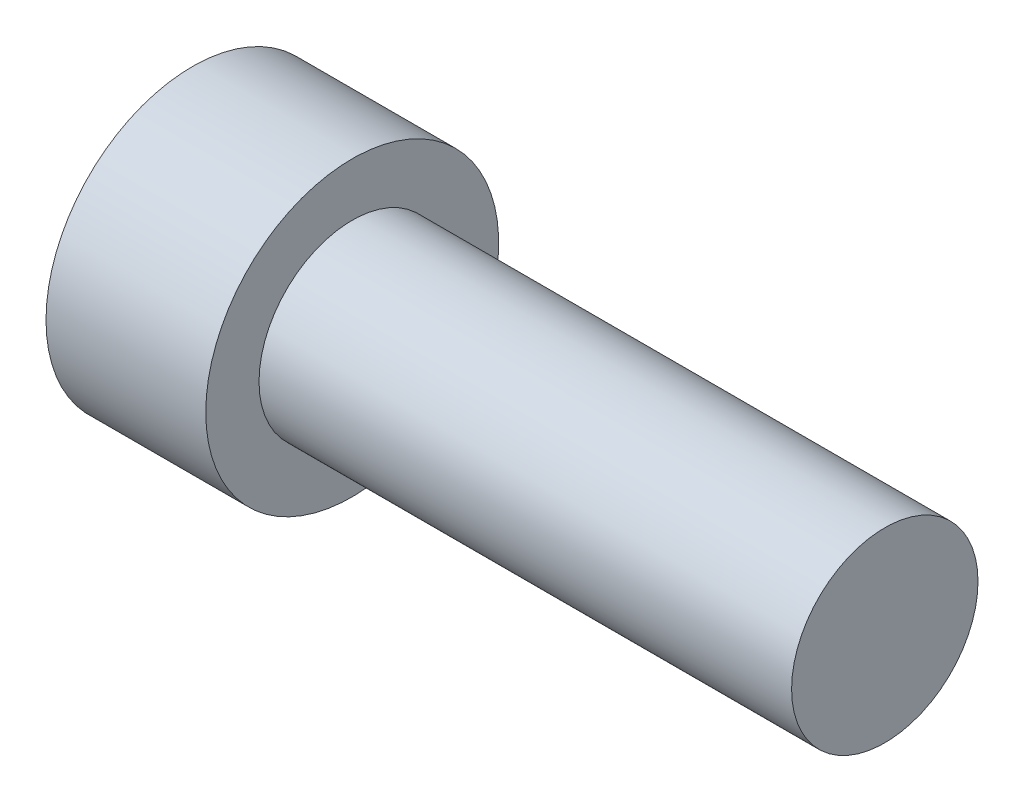
SolidWorks part; units mm, degrees
material "1023 Carbon Steel Sheet (SS)"
ref_plane "Front Plane" through (0, 0, 0) normal (0, 0, 1) x (1, 0, 0)
ref_plane "Top Plane" through (0, 0, 0) normal (0, 1, 0) x (1, 0, 0)
ref_plane "Right Plane" through (0, 0, 0) normal (1, 0, 0) x (0, 0, -1)
sketch "Sketch1" plane through (0, 0, 0) normal (1, 0, 0) x (0, 0, -1)
  circle A0 centre (0, 0) radius 1.75
  dimension "D1" = 3.5
extrude "Threaded_Screw" add sketch "Sketch1" along normal blind 10
sketch "Sketch2" plane through (0, 0, 0) normal (-1, 0, 0) x (0, 0, 1)
  circle A0 centre (0, 0) radius 2.75
  dimension "D1" = 5.5
extrude "Round_Head" add sketch "Sketch2" along normal blind 3
sketch "Sketch3" plane through (-3, 0, 0) normal (-1, 0, 0) x (0, 0, 1)
  line L0 (0, -3.025) -> (0, 3.025) construction
  line L1 (1.25, -0.7217) -> (1.25, 0.7217)
  line L2 (1.25, 0.7217) -> (0, 1.4434)
  line L3 (0, 1.4434) -> (-1.25, 0.7217)
  line L4 (-1.25, 0.7217) -> (-1.25, -0.7217)
  line L5 (-1.25, -0.7217) -> (0, -1.4434)
  line L6 (0, -1.4434) -> (1.25, -0.7217)
  circle A0 centre (0, 0) radius 1.25 construction
  dimension "D1" = 2.5
extrude "Hex_Socket_Size" cut sketch "Sketch3" against normal blind 2
